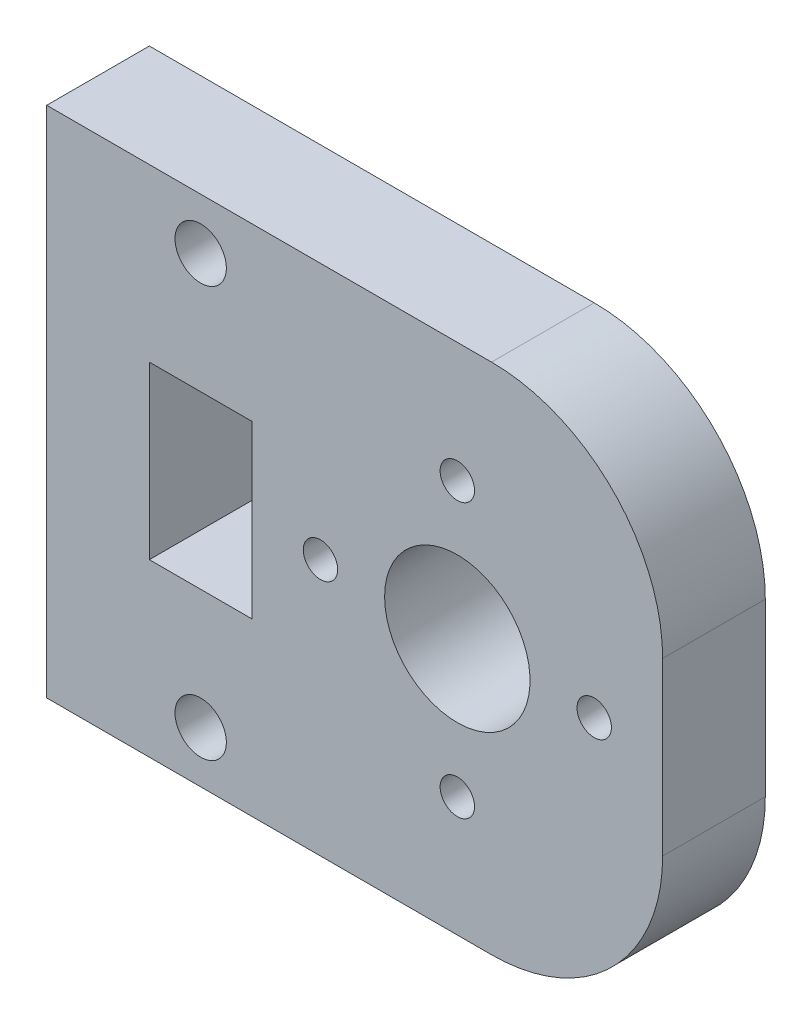
SolidWorks part; units mm, degrees
ref_plane "Plan de face" through (0, 0, 0) normal (0, 0, 1) x (1, 0, 0)
ref_plane "Plan de dessus" through (0, 0, 0) normal (0, 1, 0) x (1, 0, 0)
ref_plane "Plan de droite" through (0, 0, 0) normal (1, 0, 0) x (0, 0, -1)
sketch "Esquisse1" plane through (0, 0, 0) normal (0, 0, 1) x (1, 0, 0)
  line L1 (-24.4153, 13.2157) -> (25.5847, 13.2157)
  line L2 (-24.4153, 13.2157) -> (-24.4153, -16.7843)
  line L3 (-24.4153, -16.7843) -> (25.5847, -16.7843)
  line L4 (25.5847, 13.2157) -> (25.5847, -16.7843)
  dimension "D1" = 30
  dimension "D2" = 50
extrude "Boss.-Extru.1" add sketch "Esquisse1" along normal blind 6
sketch "Esquisse4" plane through (0, 0, 6) normal (0, 0, 1) x (1, 0, 0)
  line L0 (19.5847, 13.2157) -> (19.5847, -16.7843) construction
  line L1 (25.5847, 13.2157) -> (-24.4153, 13.2157) construction
  line L2 (-24.4153, -16.7843) -> (25.5847, -16.7843) construction
  line L3 (-19.4153, 13.2157) -> (-19.4153, -16.7843) construction
  line L4 (25.5847, -16.7843) -> (25.5847, 13.2157) construction
  line L5 (-19.4153, 13.2157) -> (-24.4153, 13.2157)
  line L6 (-24.4153, 13.2157) -> (-24.4153, -16.7843)
  line L7 (-24.4153, -16.7843) -> (-19.4153, -16.7843)
  line L8 (-19.4153, 13.2157) -> (-19.4153, -16.7843)
  dimension "D1" = 6
  dimension "D2" = 45
extrude "Enlèv. mat.-Extru.2" cut sketch "Esquisse4" against normal blind 6
sketch "Esquisse6" plane through (0, 0, 0) normal (0, 0, -1) x (-1, 0, 0)
  line L0 (19.4153, -16.7843) -> (19.4153, 13.2157) construction
  line L1 (-25.5847, -16.7843) -> (-25.5847, 13.2157) construction
  line L2 (19.4153, -16.7843) -> (-25.5847, -16.7843) construction
  line L3 (-25.5847, 13.2157) -> (19.4153, 13.2157) construction
  circle A0 centre (10.4153, 10.2157) radius 1.5
  circle A1 centre (10.4153, -13.7843) radius 1.5
  dimension "D1" = 3
  dimension "D2" = 3
  dimension "D3" = 9
  dimension "D4" = 36
  dimension "D5" = 9
  dimension "D6" = 3
  dimension "D7" = 3
extrude "Enlèv. mat.-Extru.3" cut sketch "Esquisse6" against normal blind 6
sketch "Esquisse7" plane through (0, 0, 0) normal (0, 0, -1) x (-1, 0, 0)
  circle A0 centre (10.4153, -13.7843) radius 2.995
  circle A1 centre (10.4153, 10.2157) radius 2.995
  dimension "D1" = 5.99
  dimension "D2" = 5.99
extrude "Enlèv. mat.-Extru.4" cut sketch "Esquisse7" against normal blind 3
sketch "Esquisse8" plane through (0, 0, 0) normal (0, 0, -1) x (-1, 0, 0)
  line L0 (-25.5847, 13.2157) -> (19.4153, 13.2157) construction
  line L1 (7.4153, 3.2157) -> (13.4153, 3.2157)
  line L2 (7.4153, 3.2157) -> (7.4153, -6.7843)
  line L3 (7.4153, -6.7843) -> (13.4153, -6.7843)
  line L4 (13.4153, 3.2157) -> (13.4153, -6.7843)
  line L5 (19.4153, -16.7843) -> (-25.5847, -16.7843) construction
  line L6 (19.4153, -16.7843) -> (19.4153, 13.2157) construction
  dimension "D1" = 6
  dimension "D2" = 10
  dimension "D3" = 10
  dimension "D4" = 6
extrude "Enlèv. mat.-Extru.5" cut sketch "Esquisse8" against normal blind 6
sketch "Esquisse10" plane through (0, 0, 0) normal (0, 0, -1) x (-1, 0, 0)
  line L0 (-25.5847, 13.2157) -> (19.4153, 13.2157) construction
  line L2 (19.4153, -16.7843) -> (-25.5847, -16.7843) construction
  line L3 (7.4153, 3.2157) -> (7.4153, -6.7843) construction
  line L4 (-4.5847, -16.7843) -> (-4.5847, 13.2157) construction
  line L5 (7.4153, -1.7843) -> (-25.5847, -1.7843) construction
  line L6 (-25.5847, -16.7843) -> (-25.5847, 13.2157) construction
  line L7 (19.4153, -16.7843) -> (19.4153, 13.2157) construction
  circle A1 centre (-4.5847, 6.2157) radius 1.005
  circle A2 centre (-12.5847, -1.7843) radius 1.005
  circle A3 centre (3.4153, -1.7843) radius 1.005
  circle A4 centre (-4.5847, -9.7843) radius 1.005
  dimension "D2" = 7
  dimension "D3" = 15
  dimension "D4" = 16
  dimension "D5" = 2.01
  dimension "D6" = 2.01
  dimension "D7" = 2.01
  dimension "D8" = 2.01
  dimension "D10" = 4
  dimension "D11" = 32
  dimension "D13" = 11.3137
  dimension "D14" = 11.3137
  dimension "D15" = 11.3137
  dimension "D16" = 11.3137
  dimension "D9" = 7
  dimension "D17" = 12
extrude "Enlèv. mat.-Extru.6" cut sketch "Esquisse10" against normal blind 6 contours A3 | A4 | A2 | A1
sketch "Esquisse11" plane through (0, 0, 0) normal (0, 0, -1) x (-1, 0, 0)
  line L0 (-12.5847, -1.7843) -> (3.4153, -1.7843) construction
  line L1 (-4.5847, 6.2157) -> (-4.5847, -9.7843) construction
  circle A0 centre (-4.5847, -1.7843) radius 4.25
  dimension "D1" = 8.5
extrude "Enlèv. mat.-Extru.7" cut sketch "Esquisse11" against normal blind 6
sketch "Esquisse12" plane through (0, 0, 0) normal (0, 0, -1) x (-1, 0, 0)
  line L0 (19.4153, -16.7843) -> (-25.5847, -16.7843) construction
  line L1 (-25.5847, 13.2157) -> (-16.5847, 13.2157)
  line L2 (-25.5847, 13.2157) -> (-25.5847, -16.7843)
  line L3 (-25.5847, -16.7843) -> (-16.5847, -16.7843)
  line L4 (-16.5847, 13.2157) -> (-16.5847, -16.7843)
  circle A0 centre (-12.5847, -1.7843) radius 1.005 construction
  dimension "D1" = 4
extrude "Enlèv. mat.-Extru.8" cut sketch "Esquisse12" against normal blind 6
fillet "Congé1" radius 10 2 edges at (16.5847, -16.7843, 3) (16.5847, 13.2157, 3)
